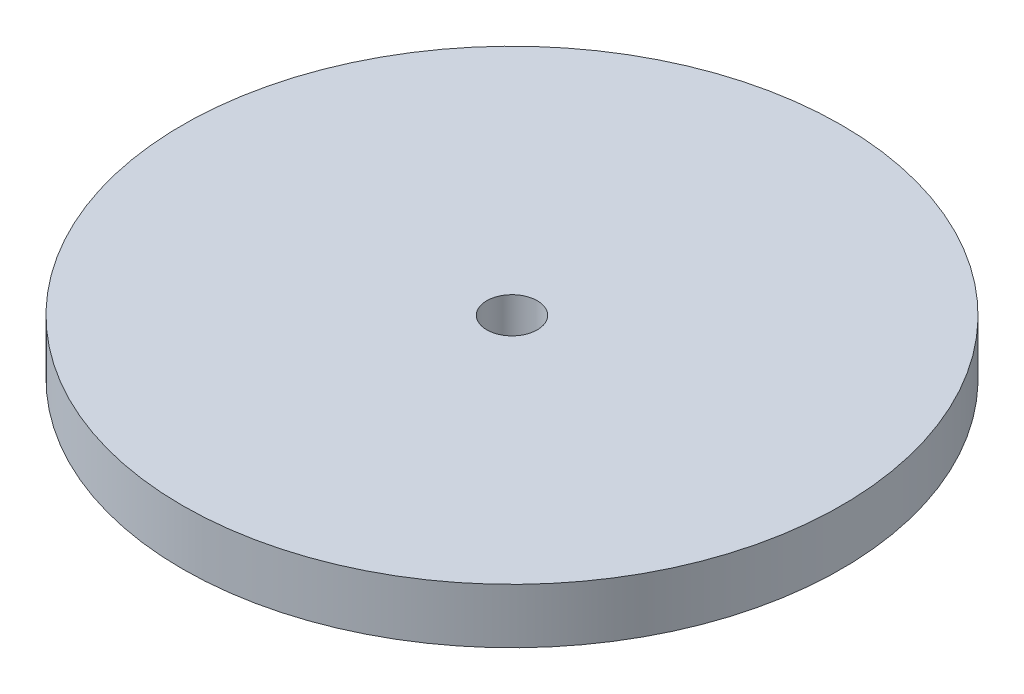
SolidWorks part; units mm, degrees
material "Acrylic (Medium-high impact)"
ref_plane "Front Plane" through (0, 0, 0) normal (0, 0, 1) x (1, 0, 0)
ref_plane "Top Plane" through (0, 0, 0) normal (0, 1, 0) x (1, 0, 0)
ref_plane "Right Plane" through (0, 0, 0) normal (1, 0, 0) x (0, 0, -1)
sketch "Sketch2" plane through (0, 0, 0) normal (0, 1, 0) x (1, 0, 0)
  circle A0 centre (0, 0) radius 19.05
  dimension "D1" = 38.1
extrude "Boss-Extrude1" add sketch "Sketch2" along normal blind 3.175
sketch "Sketch3" plane through (0, 3.175, 0) normal (0, 1, 0) x (1, 0, 0)
  circle A0 centre (0, 0) radius 1.4605
  dimension "D1" = 2.921
extrude "Cut-Extrude1" cut sketch "Sketch3" against normal through all
